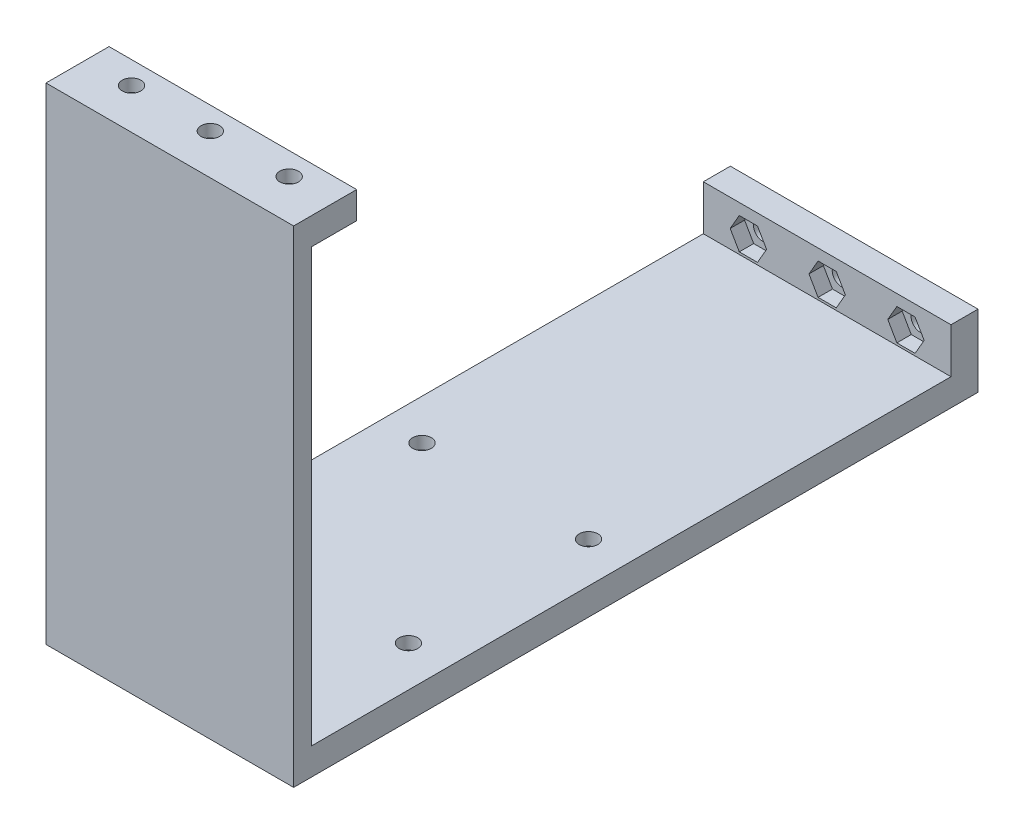
SolidWorks part; units mm, degrees
ref_plane "Front Plane" through (0, 0, 0) normal (0, 0, 1) x (1, 0, 0)
ref_plane "Top Plane" through (0, 0, 0) normal (0, 1, 0) x (1, 0, 0)
ref_plane "Right Plane" through (0, 0, 0) normal (1, 0, 0) x (0, 0, -1)
sketch "Sketch1" plane through (0, 0, 0) normal (1, 0, 0) x (0, 0, -1)
  line L0 (0, -102) -> (0, -6)
  line L1 (0, -102) -> (142, -102)
  line L2 (142, -102) -> (142, -92)
  line L3 (142, -92) -> (148, -92)
  line L4 (148, -92) -> (148, -108)
  line L5 (148, -108) -> (-4, -108)
  line L6 (-4, -108) -> (-4, 0)
  line L7 (-4, 0) -> (0, 0)
  line L8 (0, -6) -> (10, -6)
  line L9 (10, -6) -> (10, 0)
  line L10 (10, 0) -> (0, 0)
  dimension "D1" = 152
  dimension "D2" = 6
  dimension "D3" = 6
  dimension "D4" = 16
  dimension "D5" = 108
  dimension "D6" = 4
  dimension "D7" = 96
  dimension "D8" = 10
extrude "Boss-Extrude1" add sketch "Sketch1" along normal blind 55
sketch "Sketch2" plane through (0, 0, 0) normal (0, 1, 0) x (1, 0, 0)
  line L0 (0, 10) -> (0, 5) construction
  line L1 (0, 10) -> (0, -4) construction
  line L2 (0, 5) -> (10, 5) construction
  line L3 (10, 5) -> (27.5, 5) construction
  line L4 (27.5, 5) -> (45, 5) construction
  circle A0 centre (10, 5) radius 2.075
  circle A1 centre (27.5, 5) radius 2.075
  circle A2 centre (45, 5) radius 2.075
  dimension "D3" = 4.15
  dimension "D5" = 4.15
  dimension "D7" = 4.15
  dimension "D1" = 5
  dimension "D2" = 10
  dimension "D4" = 17.5
  dimension "D6" = 17.5
extrude "Cut-Extrude1" cut sketch "Sketch2" against normal up to next
sketch "Sketch3" plane through (0, 0, -148) normal (0, 0, -1) x (-1, 0, 0)
  line L0 (-55, -92) -> (-55, -98) construction
  line L1 (-55, -108) -> (-55, -92) construction
  line L2 (-55, -98) -> (-45, -98) construction
  line L3 (-45, -98) -> (-27.5, -98) construction
  line L4 (-27.5, -98) -> (-10, -98) construction
  circle A0 centre (-45, -98) radius 2.075
  circle A1 centre (-27.5, -98) radius 2.075
  circle A2 centre (-10, -98) radius 2.075
  dimension "D3" = 4.15
  dimension "D5" = 4.15
  dimension "D7" = 4.15
  dimension "D1" = 6
  dimension "D2" = 10
  dimension "D4" = 17.5
  dimension "D6" = 17.5
extrude "Cut-Extrude2" cut sketch "Sketch3" against normal up to next
sketch "Sketch4" plane through (0, -6, 0) normal (0, -1, 0) x (1, 0, 0)
  line L0 (55, -10) -> (0, -10) construction
  line L1 (49.0415, -5) -> (47.0207, -1.5)
  line L2 (47.0207, -1.5) -> (42.9793, -1.5)
  line L3 (42.9793, -1.5) -> (40.9585, -5)
  line L4 (40.9585, -5) -> (42.9793, -8.5)
  line L5 (42.9793, -8.5) -> (47.0207, -8.5)
  line L6 (47.0207, -8.5) -> (49.0415, -5)
  line L7 (29.5207, -8.5) -> (31.5415, -5)
  line L8 (31.5415, -5) -> (29.5207, -1.5)
  line L9 (29.5207, -1.5) -> (25.4793, -1.5)
  line L10 (25.4793, -1.5) -> (23.4585, -5)
  line L11 (23.4585, -5) -> (25.4793, -8.5)
  line L12 (25.4793, -8.5) -> (29.5207, -8.5)
  line L13 (14.0415, -5) -> (12.0207, -1.5)
  line L14 (12.0207, -1.5) -> (7.9793, -1.5)
  line L15 (7.9793, -1.5) -> (5.9585, -5)
  line L16 (5.9585, -5) -> (7.9793, -8.5)
  line L17 (7.9793, -8.5) -> (12.0207, -8.5)
  line L18 (12.0207, -8.5) -> (14.0415, -5)
  circle A0 centre (45, -5) radius 3.5 construction
  circle A1 centre (27.5, -5) radius 3.5 construction
  circle A2 centre (10, -5) radius 3.5 construction
  dimension "D1" = 7
  dimension "D2" = 7
  dimension "D3" = 7
extrude "Cut-Extrude3" cut sketch "Sketch4" against normal blind 3.2
sketch "Sketch5" plane through (0, 0, -142) normal (0, 0, 1) x (1, 0, 0)
  line L0 (55, -92) -> (0, -92) construction
  line L1 (14.0415, -98) -> (12.0207, -94.5)
  line L2 (12.0207, -94.5) -> (7.9793, -94.5)
  line L3 (7.9793, -94.5) -> (5.9585, -98)
  line L4 (5.9585, -98) -> (7.9793, -101.5)
  line L5 (7.9793, -101.5) -> (12.0207, -101.5)
  line L6 (12.0207, -101.5) -> (14.0415, -98)
  line L7 (31.5415, -98) -> (29.5207, -94.5)
  line L8 (29.5207, -94.5) -> (25.4793, -94.5)
  line L9 (25.4793, -94.5) -> (23.4585, -98)
  line L10 (23.4585, -98) -> (25.4793, -101.5)
  line L11 (25.4793, -101.5) -> (29.5207, -101.5)
  line L12 (29.5207, -101.5) -> (31.5415, -98)
  line L13 (47.0207, -101.5) -> (49.0415, -98)
  line L14 (49.0415, -98) -> (47.0207, -94.5)
  line L15 (47.0207, -94.5) -> (42.9793, -94.5)
  line L16 (42.9793, -94.5) -> (40.9585, -98)
  line L17 (40.9585, -98) -> (42.9793, -101.5)
  line L18 (42.9793, -101.5) -> (47.0207, -101.5)
  circle A0 centre (10, -98) radius 3.5 construction
  circle A1 centre (27.5, -98) radius 3.5 construction
  circle A2 centre (45, -98) radius 3.5 construction
  dimension "D1" = 7
  dimension "D2" = 7
  dimension "D3" = 7
extrude "Cut-Extrude4" cut sketch "Sketch5" against normal blind 3.2
sketch "Sketch6" plane through (0, -108, 0) normal (0, -1, 0) x (1, 0, 0)
  line L0 (55, 4) -> (46, 4) construction
  line L1 (55, 4) -> (0, 4) construction
  line L2 (46, 4) -> (46, -30.5) construction
  line L3 (46, -30.5) -> (46, -70.5) construction
  line L4 (27.5, 4) -> (27.5, -74.3306) construction
  circle A0 centre (46, -30.5) radius 2.075
  circle A1 centre (46, -70.5) radius 2.075
  circle A2 centre (9, -70.5) radius 2.075
  circle A3 centre (9, -30.5) radius 2.075
  dimension "D3" = 4.15
  dimension "D5" = 4.15
  dimension "D1" = 9
  dimension "D2" = 34.5
  dimension "D4" = 40
extrude "Cut-Extrude5" cut sketch "Sketch6" against normal up to next
sketch "Sketch7" plane through (0, -108, 0) normal (0, -1, 0) x (1, 0, 0)
  line L0 (27.5, 4) -> (27.5, -82.8552) construction
  line L1 (48.0207, -27) -> (43.9793, -27)
  line L2 (43.9793, -27) -> (41.9585, -30.5)
  line L3 (41.9585, -30.5) -> (43.9793, -34)
  line L4 (43.9793, -34) -> (48.0207, -34)
  line L5 (48.0207, -34) -> (50.0415, -30.5)
  line L6 (50.0415, -30.5) -> (48.0207, -27)
  line L7 (43.9793, -74) -> (48.0207, -74)
  line L8 (48.0207, -74) -> (50.0415, -70.5)
  line L9 (50.0415, -70.5) -> (48.0207, -67)
  line L10 (48.0207, -67) -> (43.9793, -67)
  line L11 (43.9793, -67) -> (41.9585, -70.5)
  line L12 (41.9585, -70.5) -> (43.9793, -74)
  line L13 (55, 4) -> (0, 4) construction
  line L14 (13.0415, -70.5) -> (11.0207, -74)
  line L15 (11.0207, -67) -> (13.0415, -70.5)
  line L16 (6.9793, -67) -> (11.0207, -67)
  line L17 (4.9585, -70.5) -> (6.9793, -67)
  line L18 (6.9793, -74) -> (4.9585, -70.5)
  line L19 (11.0207, -74) -> (6.9793, -74)
  line L20 (4.9585, -30.5) -> (6.9793, -27)
  line L21 (6.9793, -34) -> (4.9585, -30.5)
  line L22 (11.0207, -34) -> (6.9793, -34)
  line L23 (13.0415, -30.5) -> (11.0207, -34)
  line L24 (11.0207, -27) -> (13.0415, -30.5)
  line L25 (6.9793, -27) -> (11.0207, -27)
  circle A0 centre (46, -30.5) radius 3.5 construction
  circle A1 centre (46, -70.5) radius 3.5 construction
  circle A2 centre (9, -70.5) radius 3.5 construction
  circle A3 centre (9, -30.5) radius 3.5 construction
  dimension "D1" = 7
  dimension "D2" = 7
extrude "Cut-Extrude6" cut sketch "Sketch7" against normal blind 3.2
